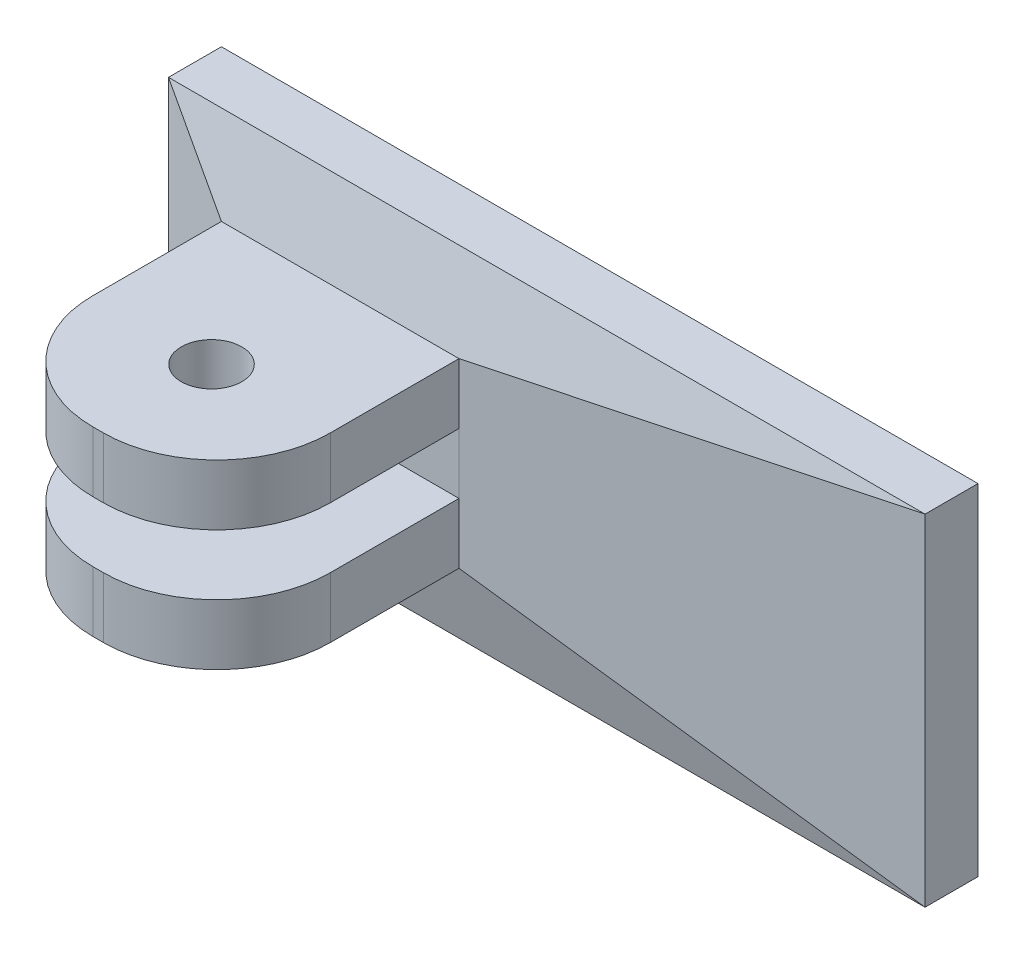
SolidWorks part; units mm, degrees
ref_plane "Front Plane" through (0, 0, 0) normal (0, 0, 1) x (1, 0, 0)
ref_plane "Top Plane" through (0, 0, 0) normal (0, 1, 0) x (1, 0, 0)
ref_plane "Right Plane" through (0, 0, 0) normal (1, 0, 0) x (0, 0, -1)
sketch "Sketch1" plane through (0, 0, 0) normal (0, 0, 1) x (1, 0, 0)
  line L0 (-36.8379, 0) -> (35.7924, 0) construction
  line L1 (-9.658, 0) -> (9.6311, 0) construction
  line L2 (0, 28.0357) -> (0, -21.5283) construction
  line L16 (-23.95, 14.8522) -> (76.05, 14.8522)
  line L17 (-23.95, 14.8522) -> (-23.95, -30.1478)
  line L18 (-23.95, -30.1478) -> (76.05, -30.1478)
  line L19 (76.05, 14.8522) -> (76.05, -30.1478)
  dimension "D1" = 100
  dimension "D2" = 45
extrude "Boss-Extrude1" add sketch "Sketch1" along normal blind 10
sketch "Sketch3" plane through (0, 0, 10) normal (0, 0, 1) x (1, 0, 0)
  line L0 (76.05, 14.8522) -> (-23.95, 14.8522) construction
  line L1 (-13.95, 4.8522) -> (17.45, 4.8522)
  line L2 (-13.95, 4.8522) -> (-13.95, -3.1478)
  line L3 (-13.95, -3.1478) -> (17.45, -3.1478)
  line L4 (17.45, 4.8522) -> (17.45, -3.1478)
  line L5 (-23.95, 14.8522) -> (-23.95, -30.1478) construction
  dimension "D1" = 31.4
  dimension "D2" = 8
  dimension "D3" = 10
  dimension "D4" = 10
extrude "Boss-Extrude2" add sketch "Sketch3" along normal blind 5
sketch "Sketch4" plane through (0, -3.1478, 0) normal (0, -1, 0) x (1, 0, 0)
  line L0 (-13.95, 15) -> (-13.95, 27)
  line L1 (1.05, 42) -> (2.45, 42)
  line L2 (17.45, 27) -> (17.45, 15)
  line L3 (-13.95, 15) -> (17.45, 15)
  arc A0 (-13.95, 27) -> (1.05, 42) centre (1.05, 27) cw
  arc A1 (2.45, 42) -> (17.45, 27) centre (2.45, 27) cw
  circle A2 centre (1.7449, 27) radius 4
  point P11 (17.45, 42)
  dimension "D2" = 15
  dimension "D3" = 15
  dimension "D1" = 27
extrude "Boss-Extrude3" add sketch "Sketch4" against normal blind 8
ref_plane "Plane1" through (0, -7.1478, 0) normal (0, -1, 0) x (-1, 0, 0)
mirror "Mirror1" about plane through (0, -7.1478, 0) normal (0, -1, 0) of "Boss-Extrude3", "Boss-Extrude2"
sketch "Sketch5" plane through (0, -30.1478, 0) normal (0, -1, 0) x (1, 0, 0)
  line L0 (-13.95, 10) -> (-23.95, 7)
  line L1 (-23.95, 10) -> (-23.95, 0) construction
  line L2 (-23.95, 7) -> (-23.95, 10)
  line L3 (-23.95, 10) -> (-13.95, 10)
  line L4 (17.45, 10) -> (76.05, 7)
  line L5 (76.05, 10) -> (76.05, 0) construction
  line L6 (76.05, 7) -> (76.05, 10)
  line L7 (76.05, 10) -> (17.45, 10)
  dimension "D1" = 3
  dimension "D2" = 3
extrude "Cut-Extrude1" cut sketch "Sketch5" against normal blind 45
sketch "Sketch6" plane through (-23.95, 0, 0) normal (-1, 0, 0) x (0, 0, 1)
  line L0 (7, 14.8522) -> (10, 4.8522)
  line L1 (10, 4.8522) -> (10, 14.8522)
  line L2 (10, 14.8522) -> (7, 14.8522)
  line L3 (10, -19.1478) -> (7, -30.1478)
  line L4 (7, -30.1478) -> (10, -30.1478)
  line L5 (10, -30.1478) -> (10, -19.1478)
extrude "Cut-Extrude2" cut sketch "Sketch6" against normal blind 100
